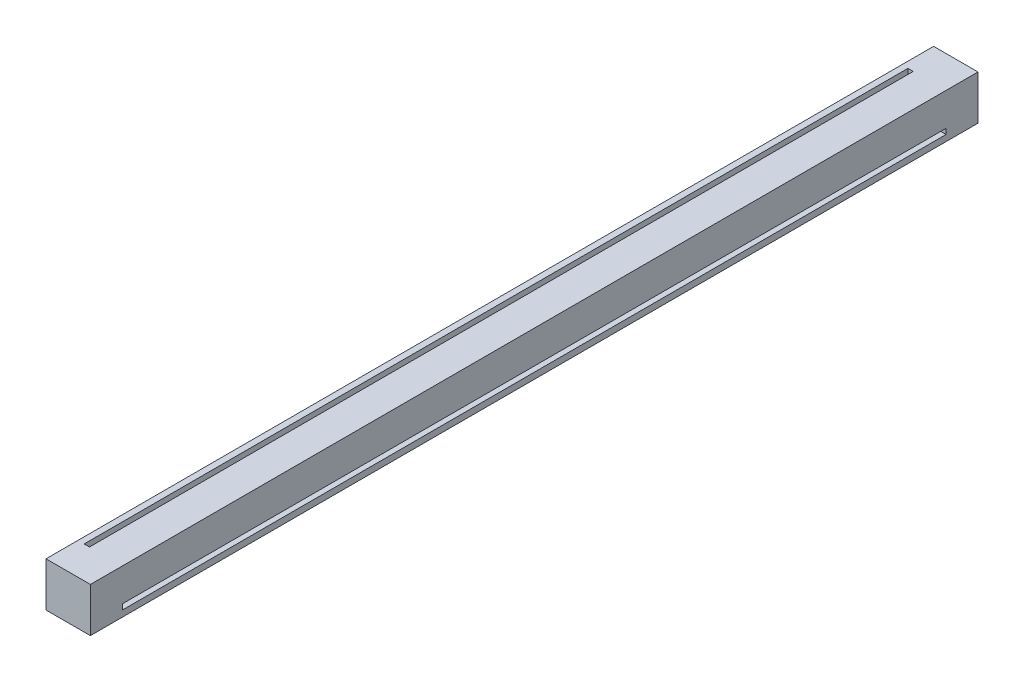
SolidWorks part; units mm, degrees
ref_plane "Płaszczyzna przednia" through (0, 0, 0) normal (0, 0, 1) x (1, 0, 0)
ref_plane "Płaszczyzna górna" through (0, 0, 0) normal (0, 1, 0) x (1, 0, 0)
ref_plane "Płaszczyzna prawa" through (0, 0, 0) normal (1, 0, 0) x (0, 0, -1)
sketch "Szkic1" plane through (0, 0, 0) normal (0, 0, 1) x (1, 0, 0)
  line L1 (0, 0) -> (25, 0)
  line L2 (0, 0) -> (0, 25)
  line L3 (0, 25) -> (25, 25)
  line L4 (25, 0) -> (25, 25)
  dimension "D1" = 25
extrude "Dodanie-wyciągnięcie1" add sketch "Szkic1" along normal blind 500
sketch "Szkic2" plane through (0, 25, 0) normal (0, 1, 0) x (1, 0, 0)
  line L1 (6.5, -482) -> (3.5, -482)
  line L2 (6.5, -482) -> (6.5, -18)
  line L3 (6.5, -18) -> (3.5, -18)
  line L4 (3.5, -482) -> (3.5, -18)
  line L6 (0, -500) -> (0, 0) construction
  line L8 (25, 0) -> (0, 0) construction
  line L9 (25, -500) -> (0, -500) construction
  dimension "D1" = 3
  dimension "D2" = 3.5
  dimension "D3" = 18
  dimension "D4" = 18
extrude "Wytnij-wyciągnięcie1" cut sketch "Szkic2" against normal blind 3
sketch "Szkic3" plane through (25, 0, 0) normal (1, 0, 0) x (0, 0, -1)
  line L0 (-500, 0) -> (0, 0) construction
  line L1 (-482, 3.5) -> (-18, 3.5)
  line L2 (-482, 3.5) -> (-482, 6.5)
  line L3 (-482, 6.5) -> (-18, 6.5)
  line L4 (-18, 3.5) -> (-18, 6.5)
  line L5 (-500, 0) -> (-500, 25) construction
  line L6 (0, 0) -> (0, 25) construction
  dimension "D1" = 3.5
  dimension "D2" = 3
  dimension "D3" = 18
  dimension "D4" = 18
extrude "Wytnij-wyciągnięcie2" cut sketch "Szkic3" against normal blind 3
hole_wizard "Otwory ustalające Ø3.0mm1" positions "Szkic4" profile "Szkic5" hole size "Ø3.0" standard "Ansi Metric"
sketch "Szkic4" plane through (0, 0, 0) normal (0, 0, -1) x (-1, 0, 0)
  line L0 (0, 0) -> (-25, 0) construction
  line L2 (0, 25) -> (0, 0) construction
  point P0 (-14, 10)
  point P9 (0, 5.7693)
  point P12 (0, 0)
  dimension "D1" = 10
  dimension "D2" = 14
sketch "Szkic5" plane through (14, 10, 0) normal (1, 0, 0) x (0, 1, 0)
  line L0 (0, 0) -> (0, 16.9013)
  line L1 (0, 16.9013) -> (1.5, 16)
  line L2 (1.5, 16) -> (1.5, 0)
  line L5 (1.5, 0) -> (0, 0)
  line L10 (0, 16.9013) -> (-1.5, 16) construction
  line L11 (0, -6.35) -> (0, 107.95) construction
  dimension "Œrednica otworu" = 3
  dimension "G³êbokoœæ otworu" = 16
  dimension "K¹t wiert³a" = 118
